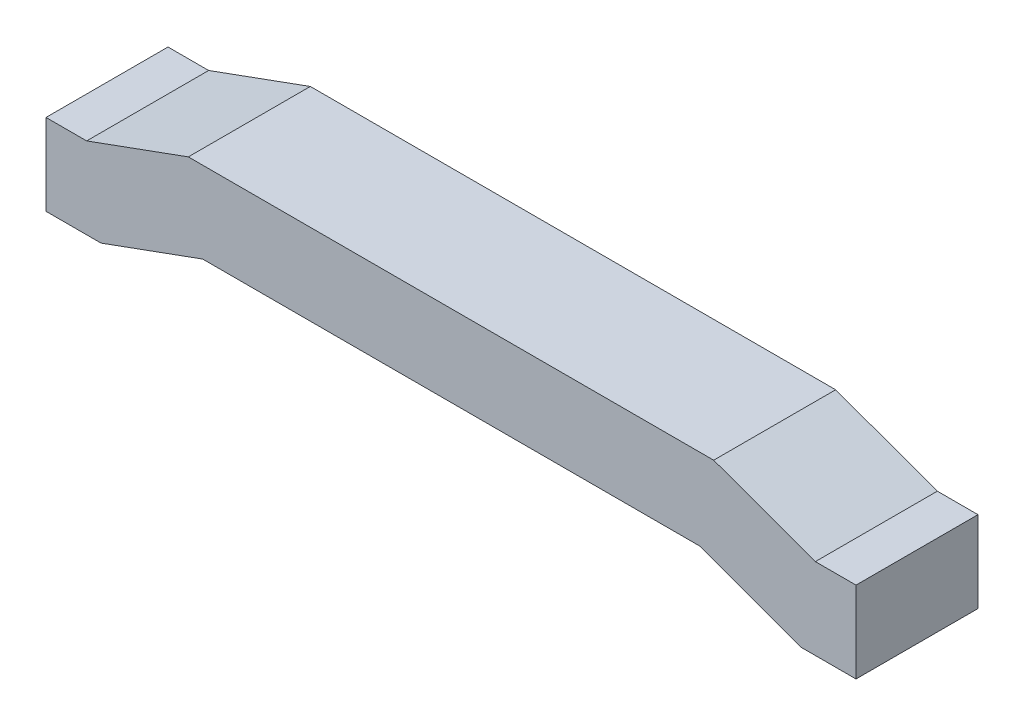
SolidWorks part; units mm, degrees
ref_plane "Front Plane" through (0, 0, 0) normal (0, 0, 1) x (1, 0, 0)
ref_plane "Top Plane" through (0, 0, 0) normal (0, 1, 0) x (1, 0, 0)
ref_plane "Right Plane" through (0, 0, 0) normal (1, 0, 0) x (0, 0, -1)
sketch "Sketch1" plane through (0, 0, 0) normal (0, 0, 1) x (1, 0, 0)
  line L0 (-508, 0) -> (508, 0) construction
  line L2 (-508, 414.8345) -> (-457.2, 414.8345)
  line L4 (503.881, 414.8345) -> (453.081, 414.8345)
  line L6 (-457.2, 414.8345) -> (-330.2, 461.0587)
  line L10 (-330.2, 461.0587) -> (184.4063, 461.0587)
  line L12 (453.081, 414.8345) -> (326.081, 461.0587)
  line L14 (184.4063, 461.0587) -> (326.081, 461.0587)
  line L16 (-508, 313.2345) -> (-439.2852, 313.2345)
  line L17 (-439.2852, 313.2345) -> (-312.2852, 359.4587)
  line L18 (-312.2852, 359.4587) -> (184.4063, 359.4587)
  line L19 (184.4063, 359.4587) -> (308.1662, 359.4587)
  line L20 (435.1662, 313.2345) -> (308.1662, 359.4587)
  line L21 (503.881, 313.2345) -> (435.1662, 313.2345)
  line L22 (-508, 414.8345) -> (-508, 313.2345)
  line L23 (503.881, 414.8345) -> (503.881, 313.2345)
  dimension "D1" = 1016
  dimension "D2" = 50.8
  dimension "D3" = 50.8
  dimension "D4" = 200
  dimension "D5" = 127
  dimension "D7" = 101.6
  dimension "D6" = 127
extrude "Boss-Extrude1" add sketch "Sketch1" along normal blind 152.4
